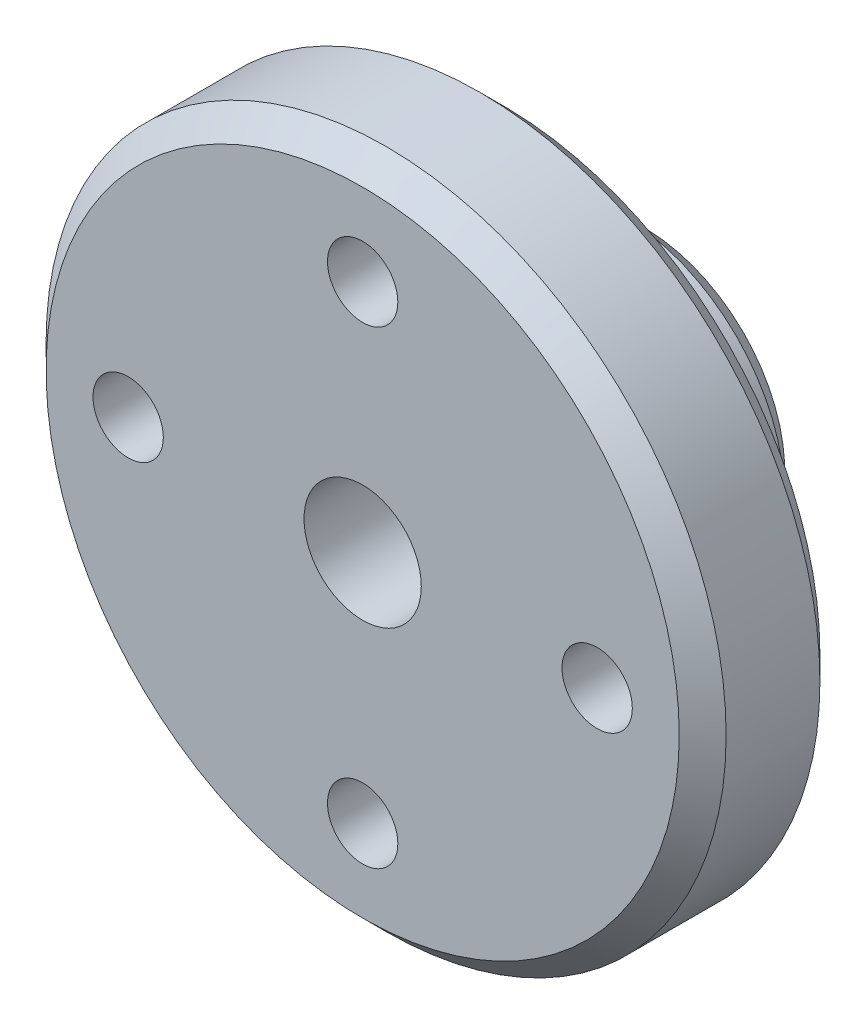
SolidWorks part; units mm, degrees
ref_plane "前视基准面" through (0, 0, 0) normal (0, 0, 1) x (1, 0, 0)
ref_plane "上视基准面" through (0, 0, 0) normal (0, 1, 0) x (1, 0, 0)
ref_plane "右视基准面" through (0, 0, 0) normal (1, 0, 0) x (0, 0, -1)
other "Configuration Table"
sketch "Sketch1" plane through (0, 0, 0) normal (0, 0, 1) x (1, 0, 0)
  circle A0 centre (0, 0) radius 7.25
  dimension "D1" = 14.5
extrude "Boss-Extrude1" add sketch "Sketch1" along normal blind 3
sketch "Sketch2" plane through (0, 0, 0) normal (0, 0, -1) x (-1, 0, 0)
  circle A0 centre (0, 0) radius 3.5
  circle A1 centre (0, 0) radius 2.5
  dimension "D1" = 7
  dimension "D2" = 5
extrude "Boss-Extrude2" add sketch "Sketch2" along normal blind 3
sketch "Sketch3" plane through (0, 0, 3) normal (0, 0, 1) x (1, 0, 0)
  circle A2 centre (0, 0) radius 5 construction
  circle A4 centre (0, 5) radius 0.75
  circle A5 centre (0, 0) radius 5 construction
  circle A6 centre (5, 0) radius 0.75
  circle A7 centre (0, 0) radius 5 construction
  circle A8 centre (0, -5) radius 0.75
  circle A9 centre (0, 0) radius 5 construction
  circle A10 centre (-5, 0) radius 0.75
  point P16 (0, 0)
  dimension "D1" = 1.5
  dimension "D2" = 10
extrude "Cut-Extrude1" cut sketch "Sketch3" against normal through all
chamfer "Chamfer1" distance 0.5 angle 45 3 edges at (-3.5, 0, -3) (7.25, 0, 3) (7.25, 0, 0)
sketch "Sketch5" plane through (0, 0, 3) normal (0, 0, 1) x (1, 0, 0)
  circle A0 centre (0, 0) radius 1.25
  dimension "D1" = 2.5
extrude "Cut-Extrude3" cut sketch "Sketch5" against normal through all
